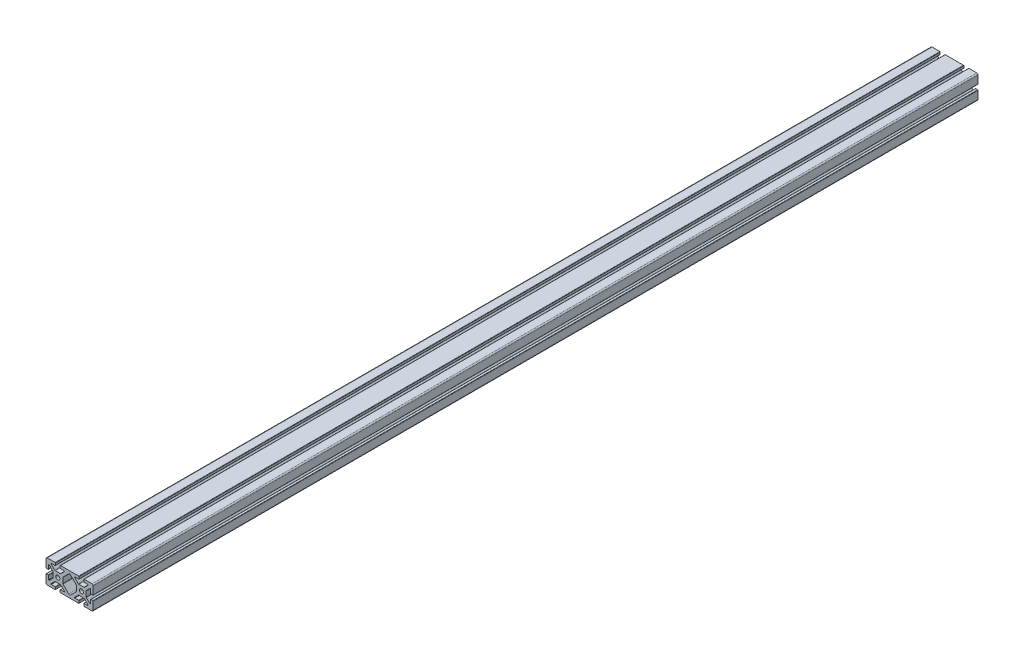
SolidWorks part; units mm, degrees
material "1060 Alloy"
ref_plane "Front Plane" through (0, 0, 0) normal (0, 0, 1) x (1, 0, 0)
ref_plane "Top Plane" through (0, 0, 0) normal (0, 1, 0) x (1, 0, 0)
ref_plane "Right Plane" through (0, 0, 0) normal (1, 0, 0) x (0, 0, -1)
sketch "Sketch1" plane through (0, 0, 0) normal (0, 0, 1) x (1, 0, 0)
  line L6 (11.2056, -5.1821) -> (1.4849, -14.9028)
  line L7 (-11.2056, -5.1821) -> (-1.4849, -14.9028)
  line L8 (-11.5571, 4.3336) -> (-11.5571, -4.3336)
  line L9 (-11.2056, 5.1821) -> (-1.4849, 14.9028)
  line L10 (11.2056, 5.1821) -> (1.4849, 14.9028)
  line L11 (11.5571, 4.3336) -> (11.5571, -4.3336)
  line L122 (-30.9, 15.5179) -> (-24.6, 15.5179)
  line L123 (-24, 16.1179) -> (-24, 19.4)
  line L124 (-24.6, 20) -> (-37.9, 20)
  line L125 (-40, 17.9) -> (-40, 4.6)
  line L126 (-39.4, 4) -> (-36.1179, 4)
  line L127 (-35.5179, 4.6) -> (-35.5179, 10.9)
  line L128 (-34.4936, 11.3243) -> (-28.3515, 5.1821)
  line L129 (-28, 4.3336) -> (-28, -4.3336)
  line L130 (-28.3515, -5.1821) -> (-34.4936, -11.3243)
  line L131 (-35.5179, -10.9) -> (-35.5179, -4.6)
  line L132 (-36.1179, -4) -> (-39.4, -4)
  line L133 (-40, -4.6) -> (-40, -17.9)
  line L134 (-37.9, -20) -> (-24.6, -20)
  line L135 (-24, -19.4) -> (-24, -16.1179)
  line L136 (-24.6, -15.5179) -> (-30.9, -15.5179)
  line L137 (-31.3243, -14.4936) -> (-25.1821, -8.3515)
  line L138 (-24.3336, -8) -> (-15.6664, -8)
  line L139 (-14.8179, -8.3515) -> (-8.6757, -14.4936)
  line L140 (-9.1, -15.5179) -> (-15.4, -15.5179)
  line L141 (-16, -16.1179) -> (-16, -19.4)
  line L142 (-15.4, -20) -> (15.4, -20)
  line L143 (16, -19.4) -> (16, -16.1179)
  line L144 (15.4, -15.5179) -> (9.1, -15.5179)
  line L145 (8.6757, -14.4936) -> (14.8179, -8.3515)
  line L146 (15.6664, -8) -> (24.3336, -8)
  line L147 (25.1821, -8.3515) -> (31.3243, -14.4936)
  line L148 (30.9, -15.5179) -> (24.6, -15.5179)
  line L149 (24, -16.1179) -> (24, -19.4)
  line L150 (24.6, -20) -> (37.9, -20)
  line L151 (40, -17.9) -> (40, -4.6)
  line L152 (39.4, -4) -> (36.1179, -4)
  line L153 (35.5179, -4.6) -> (35.5179, -10.9)
  line L154 (34.4936, -11.3243) -> (28.3515, -5.1821)
  line L155 (28, -4.3336) -> (28, 4.3336)
  line L156 (28.3515, 5.1821) -> (34.4936, 11.3243)
  line L157 (35.5179, 10.9) -> (35.5179, 4.6)
  line L158 (36.1179, 4) -> (39.4, 4)
  line L159 (40, 4.6) -> (40, 17.9)
  line L160 (37.9, 20) -> (24.6, 20)
  line L161 (24, 19.4) -> (24, 16.1179)
  line L162 (24.6, 15.5179) -> (30.9, 15.5179)
  line L163 (31.3243, 14.4936) -> (25.1821, 8.3515)
  line L164 (24.3336, 8) -> (15.6664, 8)
  line L165 (14.8179, 8.3515) -> (8.6757, 14.4936)
  line L166 (9.1, 15.5179) -> (15.4, 15.5179)
  line L167 (16, 16.1179) -> (16, 19.4)
  line L168 (15.4, 20) -> (-15.4, 20)
  line L169 (-16, 19.4) -> (-16, 16.1179)
  line L170 (-15.4, 15.5179) -> (-9.1, 15.5179)
  line L171 (-8.6757, 14.4936) -> (-14.8179, 8.3515)
  line L172 (-15.6664, 8) -> (-24.3336, 8)
  line L173 (-25.1821, 8.3515) -> (-31.3243, 14.4936)
  arc A8 (11.2056, -5.1821) -> (11.5571, -4.3336) centre (10.3571, -4.3336) ccw
  arc A9 (-1.4849, -14.9028) -> (1.4849, -14.9028) centre (0, -13.4179) ccw
  arc A10 (-11.5571, -4.3336) -> (-11.2056, -5.1821) centre (-10.3571, -4.3336) ccw
  arc A11 (-11.2056, 5.1821) -> (-11.5571, 4.3336) centre (-10.3571, 4.3336) ccw
  arc A12 (1.4849, 14.9028) -> (-1.4849, 14.9028) centre (0, 13.4179) ccw
  arc A13 (11.5571, 4.3336) -> (11.2056, 5.1821) centre (10.3571, 4.3336) ccw
  circle A14 centre (20, 0) radius 3.5
  circle A15 centre (-20, 0) radius 3.5
  arc A104 (-30.9, 15.5179) -> (-31.3243, 14.4936) centre (-30.9, 14.9179) ccw
  arc A105 (-24.6, 15.5179) -> (-24, 16.1179) centre (-24.6, 16.1179) ccw
  arc A106 (-24, 19.4) -> (-24.6, 20) centre (-24.6, 19.4) ccw
  arc A107 (-37.9, 20) -> (-40, 17.9) centre (-37.9, 17.9) ccw
  arc A108 (-40, 4.6) -> (-39.4, 4) centre (-39.4, 4.6) ccw
  arc A109 (-36.1179, 4) -> (-35.5179, 4.6) centre (-36.1179, 4.6) ccw
  arc A110 (-34.4936, 11.3243) -> (-35.5179, 10.9) centre (-34.9179, 10.9) ccw
  arc A111 (-28, 4.3336) -> (-28.3515, 5.1821) centre (-29.2, 4.3336) ccw
  arc A112 (-28.3515, -5.1821) -> (-28, -4.3336) centre (-29.2, -4.3336) ccw
  arc A113 (-35.5179, -10.9) -> (-34.4936, -11.3243) centre (-34.9179, -10.9) ccw
  arc A114 (-35.5179, -4.6) -> (-36.1179, -4) centre (-36.1179, -4.6) ccw
  arc A115 (-39.4, -4) -> (-40, -4.6) centre (-39.4, -4.6) ccw
  arc A116 (-40, -17.9) -> (-37.9, -20) centre (-37.9, -17.9) ccw
  arc A117 (-24.6, -20) -> (-24, -19.4) centre (-24.6, -19.4) ccw
  arc A118 (-24, -16.1179) -> (-24.6, -15.5179) centre (-24.6, -16.1179) ccw
  arc A119 (-31.3243, -14.4936) -> (-30.9, -15.5179) centre (-30.9, -14.9179) ccw
  arc A120 (-24.3336, -8) -> (-25.1821, -8.3515) centre (-24.3336, -9.2) ccw
  arc A121 (-14.8179, -8.3515) -> (-15.6664, -8) centre (-15.6664, -9.2) ccw
  arc A122 (-9.1, -15.5179) -> (-8.6757, -14.4936) centre (-9.1, -14.9179) ccw
  arc A123 (-15.4, -15.5179) -> (-16, -16.1179) centre (-15.4, -16.1179) ccw
  arc A124 (-16, -19.4) -> (-15.4, -20) centre (-15.4, -19.4) ccw
  arc A125 (15.4, -20) -> (16, -19.4) centre (15.4, -19.4) ccw
  arc A126 (16, -16.1179) -> (15.4, -15.5179) centre (15.4, -16.1179) ccw
  arc A127 (8.6757, -14.4936) -> (9.1, -15.5179) centre (9.1, -14.9179) ccw
  arc A128 (15.6664, -8) -> (14.8179, -8.3515) centre (15.6664, -9.2) ccw
  arc A129 (25.1821, -8.3515) -> (24.3336, -8) centre (24.3336, -9.2) ccw
  arc A130 (30.9, -15.5179) -> (31.3243, -14.4936) centre (30.9, -14.9179) ccw
  arc A131 (24.6, -15.5179) -> (24, -16.1179) centre (24.6, -16.1179) ccw
  arc A132 (24, -19.4) -> (24.6, -20) centre (24.6, -19.4) ccw
  arc A133 (37.9, -20) -> (40, -17.9) centre (37.9, -17.9) ccw
  arc A134 (40, -4.6) -> (39.4, -4) centre (39.4, -4.6) ccw
  arc A135 (36.1179, -4) -> (35.5179, -4.6) centre (36.1179, -4.6) ccw
  arc A136 (34.4936, -11.3243) -> (35.5179, -10.9) centre (34.9179, -10.9) ccw
  arc A137 (28, -4.3336) -> (28.3515, -5.1821) centre (29.2, -4.3336) ccw
  arc A138 (28.3515, 5.1821) -> (28, 4.3336) centre (29.2, 4.3336) ccw
  arc A139 (35.5179, 10.9) -> (34.4936, 11.3243) centre (34.9179, 10.9) ccw
  arc A140 (35.5179, 4.6) -> (36.1179, 4) centre (36.1179, 4.6) ccw
  arc A141 (39.4, 4) -> (40, 4.6) centre (39.4, 4.6) ccw
  arc A142 (40, 17.9) -> (37.9, 20) centre (37.9, 17.9) ccw
  arc A143 (24.6, 20) -> (24, 19.4) centre (24.6, 19.4) ccw
  arc A144 (24, 16.1179) -> (24.6, 15.5179) centre (24.6, 16.1179) ccw
  arc A145 (31.3243, 14.4936) -> (30.9, 15.5179) centre (30.9, 14.9179) ccw
  arc A146 (24.3336, 8) -> (25.1821, 8.3515) centre (24.3336, 9.2) ccw
  arc A147 (14.8179, 8.3515) -> (15.6664, 8) centre (15.6664, 9.2) ccw
  arc A148 (9.1, 15.5179) -> (8.6757, 14.4936) centre (9.1, 14.9179) ccw
  arc A149 (15.4, 15.5179) -> (16, 16.1179) centre (15.4, 16.1179) ccw
  arc A150 (16, 19.4) -> (15.4, 20) centre (15.4, 19.4) ccw
  arc A151 (-15.4, 20) -> (-16, 19.4) centre (-15.4, 19.4) ccw
  arc A152 (-16, 16.1179) -> (-15.4, 15.5179) centre (-15.4, 16.1179) ccw
  arc A153 (-8.6757, 14.4936) -> (-9.1, 15.5179) centre (-9.1, 14.9179) ccw
  arc A154 (-15.6664, 8) -> (-14.8179, 8.3515) centre (-15.6664, 9.2) ccw
  arc A155 (-25.1821, 8.3515) -> (-24.3336, 8) centre (-24.3336, 9.2) ccw
extrude "Boss-Extrude1" add sketch "Sketch1" along normal mid plane 1500
